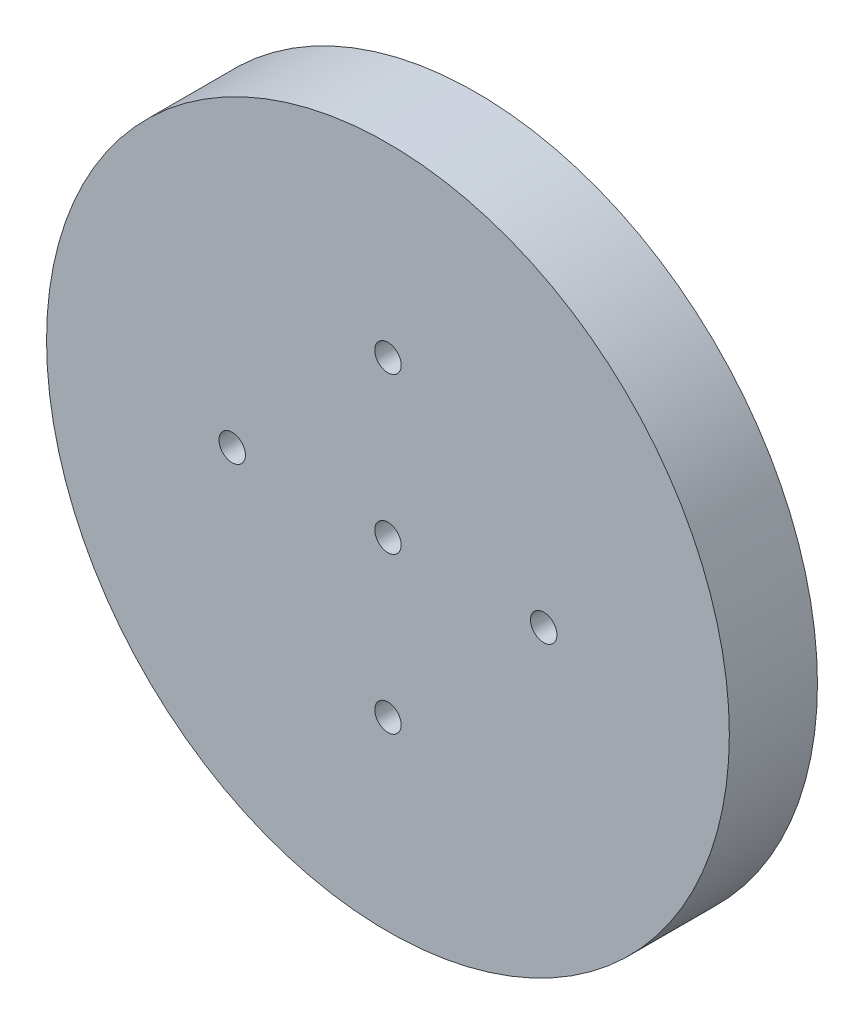
SolidWorks part; units mm, degrees
ref_plane "前视基准面" through (0, 0, 0) normal (0, 0, 1) x (1, 0, 0)
ref_plane "上视基准面" through (0, 0, 0) normal (0, 1, 0) x (1, 0, 0)
ref_plane "右视基准面" through (0, 0, 0) normal (1, 0, 0) x (0, 0, -1)
sketch "草图1" plane through (0, 0, 0) normal (0, 0, 1) x (1, 0, 0)
  circle A0 centre (0, 0) radius 38.75
  dimension "D1" = 77.5
extrude "凸台-拉伸1" add sketch "草图1" along normal blind 10
sketch "草图2" plane through (0, 0, 0) normal (0, 0, -1) x (-1, 0, 0)
  circle A0 centre (0, 0) radius 37
  dimension "D1" = 74
extrude "切除-拉伸1" cut sketch "草图2" against normal blind 7
sketch "草图3" plane through (0, 0, 7) normal (0, 0, -1) x (-1, 0, 0)
  circle A0 centre (0, 0) radius 10
  dimension "D1" = 20
extrude "凸台-拉伸2" add sketch "草图3" along normal blind 1
sketch "草图4" plane through (0, 0, 10) normal (0, 0, 1) x (1, 0, 0)
  line L0 (-60.9278, 0) -> (72.5662, 0) construction
  line L1 (0, 46.9988) -> (0, -55.6743) construction
  line L2 (-17.6777, 0) -> (0, -17.6777)
  line L3 (0, 17.6777) -> (17.6777, 0)
  line L4 (0, -17.6777) -> (17.6777, 0)
  line L5 (-17.6777, 0) -> (0, 17.6777)
  circle A0 centre (0, 17.6777) radius 1.5
  circle A1 centre (17.6777, 0) radius 1.5
  circle A2 centre (0, -17.6777) radius 1.5
  circle A3 centre (-17.6777, 0) radius 1.5
  circle A4 centre (0, 0) radius 1.5
  dimension "D1" = 3
  dimension "D2" = 25
  dimension "D3" = 3
  dimension "D4" = 25
  dimension "D5" = 90
extrude "切除-拉伸2" cut sketch "草图4" against normal through all contours A2 | A1 | A0 | A3 | A4
